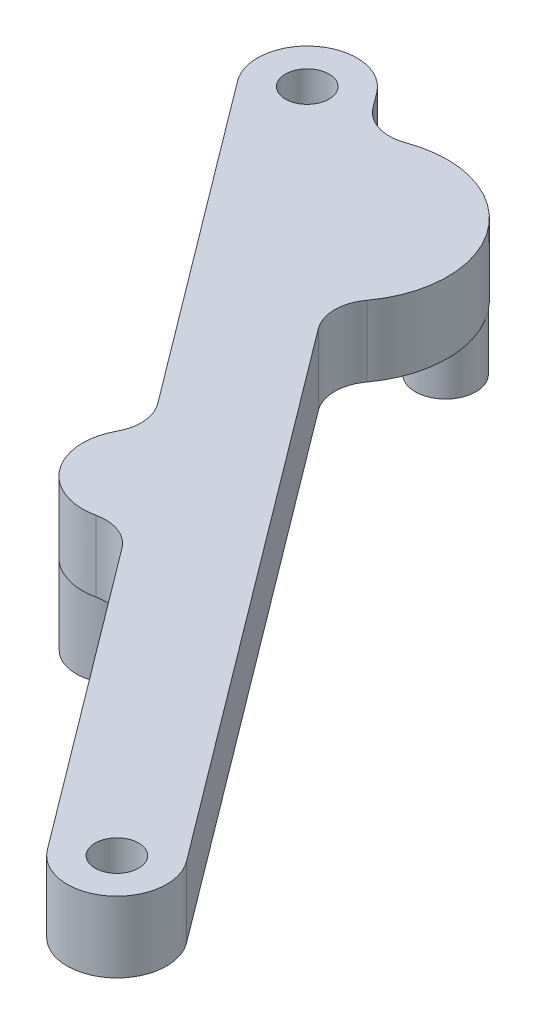
SolidWorks part; units mm, degrees
ref_plane "Front Plane" through (0, 0, 0) normal (0, 0, 1) x (1, 0, 0)
ref_plane "Top Plane" through (0, 0, 0) normal (0, 1, 0) x (1, 0, 0)
ref_plane "Right Plane" through (0, 0, 0) normal (1, 0, 0) x (0, 0, -1)
sketch "Sketch1" plane through (0, 0, 0) normal (0, 1, 0) x (1, 0, 0)
  line L0 (13.5717, 65.254) -> (31.1777, 41.7793)
  line L1 (19.4117, 69.634) -> (20.2558, 68.5085)
  line L2 (30.4617, 63.634) -> (26.2697, 60.49)
  line L3 (34.1447, 35.821) -> (35.1058, 36.5418)
  line L4 (39.0339, 31.3044) -> (55.4817, 9.374)
  line L5 (33.4564, 38.741) -> (36.7552, 34.3427)
  line L6 (32.2836, 52.4715) -> (61.3217, 13.754)
  circle A0 centre (16.4917, 67.444) radius 1.6
  circle A1 centre (58.4017, 11.564) radius 1.6
  arc A2 (55.4817, 9.374) -> (61.3217, 13.754) centre (58.4017, 11.564) ccw
  arc A3 (19.4117, 69.634) -> (13.5717, 65.254) centre (16.4917, 67.444) ccw
  circle A4 centre (34.1447, 35.821) radius 3
  circle A5 centre (30.4617, 63.634) radius 2.2225
  arc A6 (32.271, 56.0546) -> (23.692, 67.4932) centre (26.2697, 60.49) ccw
  arc A7 (31.4139, 38.5473) -> (35.9973, 32.4361) centre (35.1058, 36.5418) ccw
  arc A8 (31.4139, 38.5473) -> (31.1777, 41.7793) centre (28.7777, 39.9793) ccw
  arc A9 (35.9973, 32.4361) -> (39.0339, 31.3044) centre (36.6339, 29.5044) cw
  arc A10 (23.692, 67.4932) -> (20.2558, 68.5085) centre (22.6558, 70.3085) cw
  arc A11 (32.271, 56.0546) -> (32.2836, 52.4715) centre (34.6836, 54.2715) ccw
  point P27 (37.6267, 33.1807)
  point P32 (30.7472, 54.52)
  dimension "D3" = 3.2
  dimension "D4" = 3.2
  dimension "D5" = 7.3
  dimension "D6" = 7.3
  dimension "D11" = 4.445
  dimension "D12" = 6
  dimension "D13" = 6
  dimension "D14" = 3
  dimension "D15" = 3
  dimension "D1" = 41.91
  dimension "D2" = 55.88
  dimension "D7" = 24.257
  dimension "D8" = 24.257
  dimension "D9" = 27.94
  dimension "D10" = 52.07
extrude "Boss-Extrude1" add sketch "Sketch1" along normal blind 5.2
sketch "Sketch2" plane through (0, 0, 0) normal (0, -1, 0) x (1, 0, 0)
  circle A0 centre (34.1447, -35.821) radius 3
  dimension "D1" = 6
extrude "Boss-Extrude2" add sketch "Sketch2" along normal blind 6
sketch "Sketch3" plane through (0, 0, 0) normal (0, -1, 0) x (1, 0, 0)
  circle A0 centre (30.4617, -63.634) radius 2.2225
  dimension "D1" = 4.445
extrude "Boss-Extrude3" add sketch "Sketch3" along normal blind 4.21
